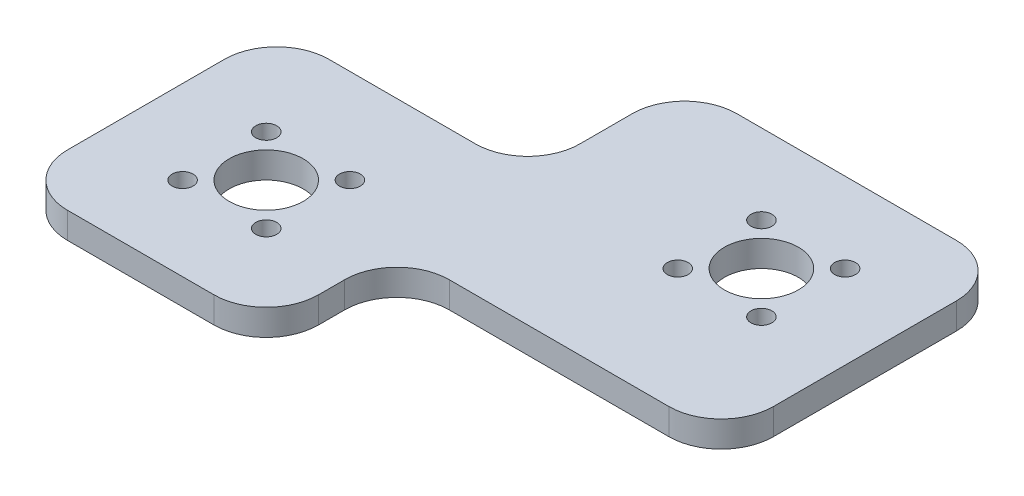
SolidWorks part; units mm, degrees
ref_plane "Front Plane" through (0, 0, 0) normal (0, 0, 1) x (1, 0, 0)
ref_plane "Top Plane" through (0, 0, 0) normal (0, 1, 0) x (1, 0, 0)
ref_plane "Right Plane" through (0, 0, 0) normal (1, 0, 0) x (0, 0, -1)
sketch "Sketch1" plane through (0, 0, 0) normal (0, 1, 0) x (1, 0, 0)
  line L1 (-88.9262, 16.9463) -> (-40.9262, 16.9463)
  line L2 (-88.9262, 16.9463) -> (-88.9262, -33.0537)
  line L11 (-40.9262, -33.0537) -> (-88.9262, -33.0537)
  line L14 (-30.9262, -8.0537) -> (-13.5711, -8.0537)
  line L16 (-30.9262, -8.0537) -> (21.0738, -8.0537)
  line L18 (-30.9262, 46.9463) -> (21.0738, 46.9463)
  line L19 (21.0738, -8.0537) -> (21.0738, 46.9463)
  line L20 (-40.9262, -33.0537) -> (-40.9262, -8.0537)
  line L21 (-88.9262, -33.0537) -> (-40.9262, -33.0537)
  line L25 (-30.9262, -8.0537) -> (-40.9262, -8.0537)
  line L26 (-40.9262, 16.9463) -> (-40.9262, 46.9463)
  line L27 (-40.9262, 46.9463) -> (-30.9262, 46.9463)
  dimension "D1" = 50
  dimension "D4" = 52
  dimension "D5" = 55
extrude "Boss-Extrude1" add sketch "Sketch1" along normal blind 5
sketch "Sketch2" plane through (0, 5, 0) normal (0, 1, 0) x (1, 0, 0)
  line L2 (-88.9262, -33.0537) -> (-64.9262, -33.0537)
  line L4 (-88.9262, -33.0537) -> (-88.9262, -9.0537)
  circle A0 centre (-2.9262, 23.6432) radius 7.075
  circle A1 centre (-10.9262, 31.6432) radius 2
  circle A2 centre (5.0738, 31.6432) radius 2
  circle A3 centre (5.0738, 15.6432) radius 2
  circle A4 centre (-10.9262, 15.6432) radius 2
  circle A5 centre (-64.9262, -9.0537) radius 7.075
  circle A6 centre (-72.9262, -1.0537) radius 2
  circle A7 centre (-56.9262, -1.0537) radius 2
  circle A8 centre (-56.9262, -17.0537) radius 2
  circle A9 centre (-72.9262, -17.0537) radius 2
  dimension "D3" = 4
  dimension "D6" = 14.15
  dimension "D8" = 4
  dimension "D1" = 24
  dimension "D2" = 24
  dimension "D4" = 2
  dimension "D5" = 2
  dimension "D9" = 2
  dimension "D10" = 2
extrude "Cut-Extrude1" cut sketch "Sketch2" against normal blind 5 contours A5 | A6 | A7 | A8 | A9 | A0 | A2 | A4 | A1 | A3
fillet "Fillet1" radius 10 1 edges at (-88.9262, 2.5, -16.9463)
fillet "Fillet2" radius 10 7 edges at (-88.9262, 2.5, 33.0537) (-40.9262, 2.5, 33.0537) (-40.9262, 2.5, 8.0537) (21.0738, 2.5, 8.0537) (21.0738, 2.5, -46.9463) (-40.9262, 2.5, -46.9463) (-40.9262, 2.5, -16.9463)
